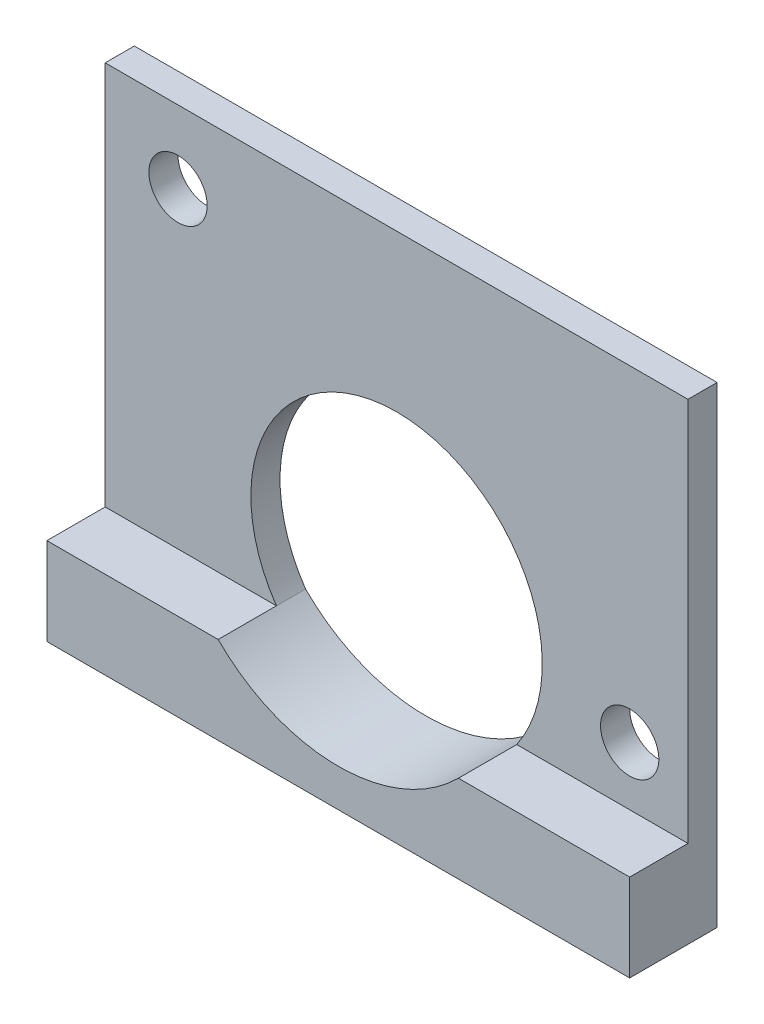
SolidWorks part; units mm, degrees
ref_plane "Alzado" through (0, 0, 0) normal (0, 0, 1) x (1, 0, 0)
ref_plane "Planta" through (0, 0, 0) normal (0, 1, 0) x (1, 0, 0)
ref_plane "Vista lateral" through (0, 0, 0) normal (1, 0, 0) x (0, 0, -1)
sketch "Croquis1" plane through (0, 0, 0) normal (0, 0, 1) x (1, 0, 0)
  line L1 (-79.0345, 42.2856) -> (-79.0345, 34.2856)
  line L3 (-99.0345, 34.2856) -> (-99.0345, 42.2856)
  line L4 (-96.0345, 39.9136) -> (-82.0345, 39.9136) construction
  line L5 (-89.0345, 39.9136) -> (-89.0345, 43.9136) construction
  line L6 (-79.0345, 42.2856) -> (-79.0345, 54.2856)
  line L7 (-79.0345, 54.2856) -> (-99.0345, 54.2856)
  line L8 (-99.0345, 54.2856) -> (-99.0345, 42.2856)
  line L9 (-89.0345, 34.2856) -> (-85.5345, 34.2856) construction
  line L10 (-89.0345, 34.2856) -> (-92.5345, 34.2856) construction
  line L13 (-79.0345, 34.2856) -> (-85.5345, 34.2856)
  line L16 (-92.5345, 34.2856) -> (-99.0345, 34.2856)
  line L17 (-85.5345, 34.2856) -> (-85.5345, 43.9136)
  line L18 (-92.5345, 34.2856) -> (-92.5345, 43.9136)
  circle A0 centre (-96.0345, 38.2856) radius 1.628
  circle A1 centre (-82.0345, 38.2856) radius 1.628
  arc A7 (-85.5345, 43.9136) -> (-92.5345, 43.9136) centre (-89.0345, 43.9136) ccw
  dimension "D1" = 14
  dimension "D2" = 20
  dimension "D3" = 8
  dimension "D4" = 3
extrude "Saliente-Extruir1" add sketch "Croquis1" along normal blind 4
sketch "Croquis2" plane through (0, 0, 0) normal (0, 0, -1) x (-1, 0, 0)
  line L0 (79.0345, 41.0856) -> (83.6296, 41.0856)
  line L1 (79.0345, 34.2856) -> (79.0345, 54.2856) construction
  line L2 (94.4393, 41.0856) -> (99.0345, 41.0856)
  line L3 (99.0345, 54.2856) -> (99.0345, 34.2856) construction
  line L4 (89.0345, 50.0136) -> (89.0345, 54.2856) construction
  line L5 (79.0345, 54.2856) -> (99.0345, 54.2856) construction
  line L6 (89.0345, 54.2856) -> (85.0345, 54.2856) construction
  line L7 (79.0345, 41.0856) -> (79.0345, 54.2856)
  line L8 (79.0345, 54.2856) -> (99.0345, 54.2856)
  line L9 (99.0345, 54.2856) -> (99.0345, 41.0856)
  arc A2 (83.6296, 41.0856) -> (94.4393, 41.0856) centre (89.0345, 43.9136) cw
extrude "Saliente-Extruir2" add sketch "Croquis2" along normal blind 9
sketch "Croquis3" plane through (0, 54.2856, 0) normal (0, 1, 0) x (1, 0, 0)
  line L0 (-89.0345, 9) -> (-85.0345, 9) construction
  line L1 (-99.0345, 9) -> (-79.0345, 9) construction
  line L2 (-85.0345, 9) -> (-85.0345, -4) construction
  line L3 (-79.0345, -4) -> (-99.0345, -4) construction
  line L4 (-85.0345, -4) -> (-85.0345, -3) construction
  line L5 (-85.0345, -3) -> (-85.0345, 12) construction
  line L6 (-85.0345, 12) -> (-85.0345, 7) construction
  line L7 (-85.0345, 7) -> (-90.0345, 7) construction
  line L8 (-85.0345, 7) -> (-80.0345, 7) construction
  line L9 (-79.0345, 8.118) -> (-79.0345, 5.882)
  line L10 (-79.0345, -4) -> (-79.0345, 9) construction
  circle A1 centre (-90.0345, 7) radius 1.5
  arc A3 (-79.0345, 8.118) -> (-79.0345, 5.882) centre (-80.0345, 7) ccw
extrude "Cortar-Extruir1" cut sketch "Croquis3" against normal blind 4
sketch "Croquis4" plane through (0, 54.2856, 0) normal (0, 1, 0) x (1, 0, 0)
  line L0 (-79.0345, -4) -> (-79.0345, 1) construction
  line L1 (-79.0345, -4) -> (-79.0345, 5.882) construction
  line L2 (-79.0345, 1) -> (-76.0345, 1) construction
  line L3 (-76.0345, 1) -> (-76.0345, 9) construction
  line L4 (-76.0345, 9) -> (-79.0345, 9) construction
  line L6 (-76.0345, 1) -> (-76.0345, 9)
  line L7 (-76.0345, 9) -> (-79.0345, 9)
  line L11 (-79.0345, 9) -> (-79.0345, 8.118)
  line L14 (-79.0345, 5.882) -> (-79.0345, -4)
  line L16 (-79.0345, -4) -> (-76.0345, 1)
  arc A4 (-79.0345, 5.882) -> (-79.0345, 8.118) centre (-80.0345, 7) ccw
extrude "Saliente-Extruir3" add sketch "Croquis4" against normal blind 7
sketch "Croquis5" plane through (0, 0, -9) normal (0, 0, -1) x (-1, 0, 0)
  line L0 (99.0345, 54.2856) -> (90.0345, 54.2856) construction
  line L1 (99.0345, 54.2856) -> (76.0345, 54.2856) construction
  line L2 (90.0345, 54.2856) -> (90.0345, 50.2856) construction
  line L3 (90.0345, 50.2856) -> (92.8345, 50.2856)
  line L4 (92.8345, 50.2856) -> (92.8345, 52.7856)
  line L5 (92.8345, 52.7856) -> (87.2345, 52.7856)
  line L6 (87.2345, 52.7856) -> (87.2345, 50.2856)
  line L7 (87.2345, 50.2856) -> (90.0345, 50.2856)
  line L8 (80.0345, 50.2856) -> (82.8345, 50.2856)
  line L9 (82.8345, 50.2856) -> (82.8345, 52.7856)
  line L10 (82.8345, 52.7856) -> (77.2345, 52.7856)
  line L11 (77.2345, 52.7856) -> (77.2345, 50.2856)
  line L12 (77.2345, 50.2856) -> (80.0345, 50.2856)
  dimension "D1" = 9
  dimension "D2" = 2
extrude "Cortar-Extruir2" cut sketch "Croquis5" against normal blind 4.8
sketch "Croquis10" plane through (0, 0, -9) normal (0, 0, -1) x (-1, 0, 0)
  line L0 (99.0345, 54.2856) -> (93.9712, 54.2856) construction
  line L1 (99.0345, 54.2856) -> (76.0345, 54.2856) construction
  line L2 (99.0345, 41.0856) -> (99.0345, 54.2856) construction
  line L3 (79.0345, 47.2856) -> (79.0345, 41.0856) construction
  line L4 (79.0345, 41.0856) -> (83.6296, 41.0856) construction
  circle A0 centre (96.5345, 51.7856) radius 1
  circle A1 centre (81.0345, 43.0856) radius 1
  dimension "D1" = 2.5
  dimension "D2" = 2.5
  dimension "D3" = 2
  dimension "D4" = 2
extrude "Cortar-Extruir3" cut sketch "Croquis10" against normal blind 4
sketch "Croquis11" plane through (0, 0, -9) normal (0, 0, -1) x (-1, 0, 0)
  line L0 (94.4393, 41.0856) -> (99.0345, 41.0856)
  line L1 (99.0345, 41.0856) -> (99.0345, 54.2856)
  line L2 (99.0345, 54.2856) -> (76.0345, 54.2856)
  line L3 (76.0345, 54.2856) -> (76.0345, 47.2856)
  line L4 (76.0345, 47.2856) -> (79.0345, 47.2856)
  line L5 (79.0345, 47.2856) -> (79.0345, 41.0856)
  line L6 (79.0345, 41.0856) -> (83.6296, 41.0856)
  line L7 (94.4393, 41.0856) -> (93.1579, 41.0856)
  line L8 (92.8345, 50.2856) -> (87.2345, 50.2856)
  line L9 (92.8345, 50.2856) -> (92.8345, 52.7856)
  line L10 (92.8345, 52.7856) -> (87.2345, 52.7856)
  line L11 (87.2345, 50.2856) -> (87.2345, 52.7856)
  line L12 (82.8345, 50.2856) -> (77.2345, 50.2856)
  line L13 (82.8345, 50.2856) -> (82.8345, 52.7856)
  line L14 (82.8345, 52.7856) -> (77.2345, 52.7856)
  line L15 (77.2345, 50.2856) -> (77.2345, 52.7856)
  line L16 (84.9111, 41.0856) -> (83.6296, 41.0856)
  circle A0 centre (96.5345, 51.7856) radius 1
  circle A1 centre (81.0345, 43.0856) radius 1
  arc A4 (93.1579, 41.0856) -> (84.9111, 41.0856) centre (89.0345, 43.9136) ccw
extrude "Saliente-Extruir4" add sketch "Croquis11" along normal blind 1
sketch "Croquis12" plane through (0, 0, 4) normal (0, 0, 1) x (1, 0, 0)
  line L1 (-99.0345, 34.2856) -> (-71.5312, 34.2856)
  line L2 (-99.0345, 34.2856) -> (-99.0345, 54.2856)
  line L3 (-99.0345, 54.2856) -> (-71.5312, 54.2856)
  line L4 (-71.5312, 34.2856) -> (-71.5312, 54.2856)
extrude "Cortar-Extruir4" cut sketch "Croquis12" against normal blind 13
sketch "Croquis13" plane through (0, 0, -10) normal (0, 0, -1) x (-1, 0, 0)
  line L0 (82.8345, 50.2856) -> (82.8345, 52.7856) construction
  line L1 (92.8345, 50.2856) -> (87.2345, 50.2856)
  line L2 (92.8345, 50.2856) -> (92.8345, 52.7856)
  line L3 (92.8345, 52.7856) -> (87.2345, 52.7856)
  line L4 (87.2345, 50.2856) -> (87.2345, 52.7856)
  line L5 (82.8345, 50.2856) -> (77.2345, 50.2856)
  line L6 (82.8345, 50.2856) -> (82.8345, 52.7856)
  line L7 (82.8345, 52.7856) -> (77.2345, 52.7856)
  line L8 (77.2345, 50.2856) -> (77.2345, 52.7856)
extrude "Saliente-Extruir5" add sketch "Croquis13" against normal up to vertex (1 mm away)
sketch "Croquis14" plane through (0, 0, -10) normal (0, 0, -1) x (-1, 0, 0)
  line L0 (99.0345, 41.0856) -> (99.0345, 38.0856)
  line L1 (99.0345, 38.0856) -> (79.0345, 38.0856)
  line L2 (79.0345, 38.0856) -> (79.0345, 41.0856)
  line L3 (99.0345, 41.0856) -> (93.1579, 41.0856)
  line L4 (84.9111, 41.0856) -> (79.0345, 41.0856)
  arc A0 (93.1579, 41.0856) -> (84.9111, 41.0856) centre (89.0345, 45.209) cw
extrude "Saliente-Extruir6" add sketch "Croquis14" against normal blind 3
sketch "Croquis15" plane through (0, 0, -10) normal (0, 0, -1) x (-1, 0, 0)
  line L1 (79.0345, 47.2856) -> (76.0345, 47.2856)
  line L2 (79.0345, 47.2856) -> (79.0345, 54.2856)
  line L3 (79.0345, 54.2856) -> (76.0345, 54.2856)
  line L4 (76.0345, 47.2856) -> (76.0345, 54.2856)
extrude "Cortar-Extruir5" cut sketch "Croquis15" against normal blind 3
